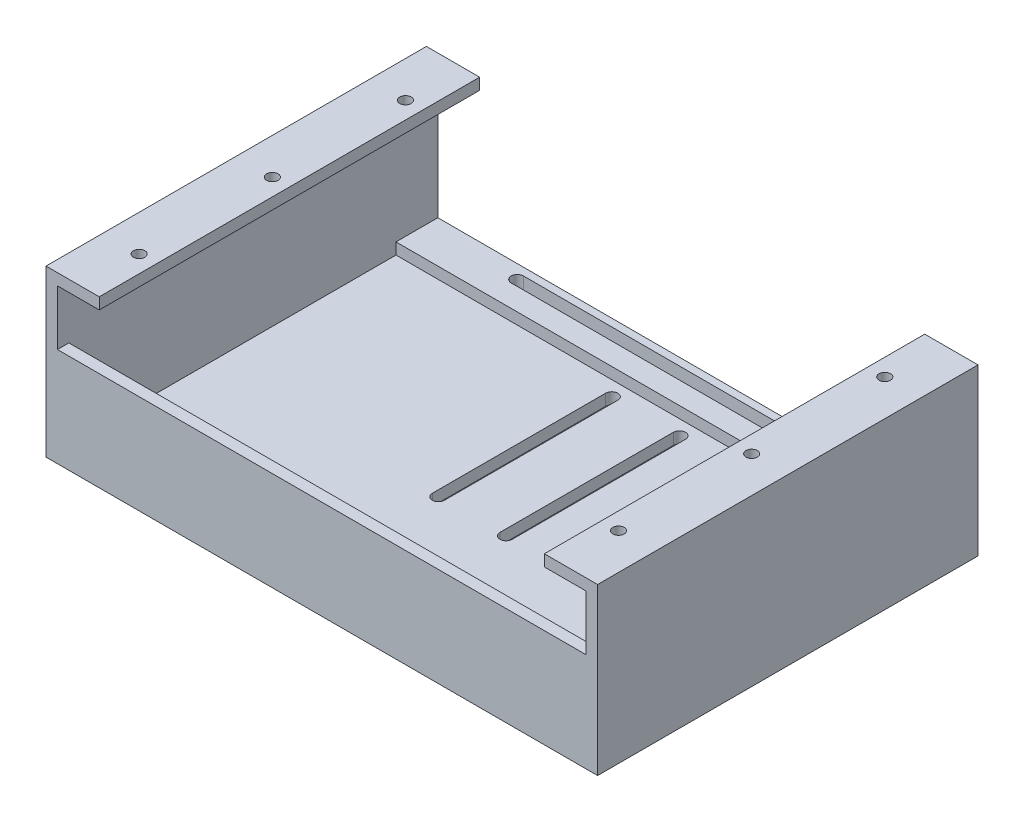
SolidWorks part; units mm, degrees
ref_plane "前视基准面" through (0, 0, 0) normal (0, 0, 1) x (1, 0, 0)
ref_plane "上视基准面" through (0, 0, 0) normal (0, 1, 0) x (1, 0, 0)
ref_plane "右视基准面" through (0, 0, 0) normal (1, 0, 0) x (0, 0, -1)
sketch "草图1" plane through (0, 0, 0) normal (0, 1, 0) x (1, 0, 0)
  line L1 (-72.5, 50) -> (72.5, 50)
  line L2 (-72.5, 50) -> (-72.5, -50)
  line L3 (-72.5, -50) -> (72.5, -50)
  line L4 (72.5, 50) -> (72.5, -50)
  line L5 (-72.5, 50) -> (72.5, -50) construction
  line L6 (-72.5, -50) -> (72.5, 50) construction
  point P0 (0, 0)
  dimension "D1" = 145
  dimension "D2" = 100
extrude "凸台-拉伸1" add sketch "草图1" along normal blind 3
sketch "草图2" plane through (0, 0, 0) normal (0, 1, 0) x (1, 0, 0)
  line L0 (-72.5, 50) -> (-69.5, 50)
  line L1 (72.5, 50) -> (-72.5, 50) construction
  line L2 (-69.5, 50) -> (-69.5, -50)
  line L3 (-72.5, -50) -> (72.5, -50) construction
  line L4 (-69.5, -50) -> (-72.5, -50)
  line L5 (-72.5, 50) -> (-72.5, -50) construction
  line L6 (-72.5, 50) -> (-72.5, -50)
  line L7 (0, 60.691) -> (0, -61.0101) construction
  line L8 (72.5, 50) -> (72.5, -50)
  line L9 (69.5, -50) -> (72.5, -50)
  line L10 (69.5, 50) -> (69.5, -50)
  line L11 (72.5, 50) -> (69.5, 50)
  dimension "D1" = 3
extrude "凸台-拉伸2" add sketch "草图2" along normal blind 40.5 from surface at 3 starting at face at (0, 3, 0)
sketch "草图3" plane through (0, 3, 0) normal (0, 1, 0) x (1, 0, 0)
  line L0 (-69.5, -50) -> (69.5, -50)
  line L1 (-69.5, -50) -> (69.5, -50) construction
  line L2 (69.5, -50) -> (69.5, -47)
  line L3 (69.5, -47) -> (-69.5, -47)
  line L4 (-69.5, 50) -> (-69.5, -50) construction
  line L5 (-69.5, -47) -> (-69.5, -50)
  dimension "D1" = 3
extrude "凸台-拉伸3" add sketch "草图3" along normal blind 23
sketch "草图4" plane through (0, 43.5, 0) normal (0, 1, 0) x (1, 0, 0)
  line L0 (-72.5, 50) -> (-58.5, 50)
  line L1 (-72.5, 50) -> (-69.5, 50) construction
  line L2 (-72.5, -50) -> (-72.5, 50) construction
  line L3 (69.5, 50) -> (-69.5, 50) construction
  line L4 (-58.5, 50) -> (-58.5, -50)
  line L5 (-69.5, -50) -> (69.5, -50) construction
  line L6 (-58.5, -50) -> (-72.5, -50)
  line L7 (-72.5, -50) -> (-72.5, 50)
  line L8 (0, 61.2498) -> (0, -56.9471) construction
  line L9 (72.5, -50) -> (72.5, 50)
  line L10 (58.5, -50) -> (72.5, -50)
  line L11 (58.5, 50) -> (58.5, -50)
  line L12 (72.5, 50) -> (58.5, 50)
  dimension "D1" = 14
extrude "凸台-拉伸4" add sketch "草图4" against normal blind 3
sketch "草图5" plane through (0, 43.5, 0) normal (0, 1, 0) x (1, 0, 0)
  line L0 (0, 70.1589) -> (0, -87.2886) construction
  line L1 (-72.5, 50) -> (-58.5, 50) construction
  line L2 (-58.5, -50) -> (-58.5, 50) construction
  circle A0 centre (-63, 35) radius 1.5
  circle A1 centre (-63, 0) radius 1.5
  circle A2 centre (-63, -35) radius 1.5
  circle A3 centre (63, -35) radius 1.5
  circle A4 centre (63, 0) radius 1.5
  circle A5 centre (63, 35) radius 1.5
  dimension "D1" = 15
  dimension "D2" = 3
  dimension "D3" = 35
  dimension "D4" = 35
  dimension "D5" = 4.5
extrude "切除-拉伸1" cut sketch "草图5" against normal up to next
sketch "草图6" plane through (0, 0, 0) normal (0, -1, 0) x (1, 0, 0)
  line L0 (0, 35.4338) -> (0, -55.998) construction
  line L1 (-8.9, 10.4483) -> (-8.9, -35.1174) construction
  line L2 (-7.3, 10.4483) -> (-7.3, -35.1174)
  line L3 (-10.5, 10.4483) -> (-10.5, -35.1174)
  line L4 (8.9, 10.4483) -> (8.9, -35.1174) construction
  line L5 (7.3, 10.4483) -> (7.3, -35.1174)
  line L6 (10.5, 10.4483) -> (10.5, -35.1174)
  arc A0 (-7.3, 10.4483) -> (-10.5, 10.4483) centre (-8.9, 10.4483) ccw
  arc A1 (-10.5, -35.1174) -> (-7.3, -35.1174) centre (-8.9, -35.1174) ccw
  arc A2 (7.3, 10.4483) -> (10.5, 10.4483) centre (8.9, 10.4483) cw
  arc A3 (10.5, -35.1174) -> (7.3, -35.1174) centre (8.9, -35.1174) cw
  point P5 (-8.9, -12.3346)
  point P12 (8.9, -12.3346)
  dimension "D1" = 1.6
  dimension "D2" = 10.5
extrude "切除-拉伸2" cut sketch "草图6" against normal up to next
sketch "草图7" plane through (69.5, 0, 0) normal (-1, 0, 0) x (0, 0, 1)
  line L0 (-50, 43.5) -> (-50, 0) construction
  line L1 (-50, 6) -> (-39, 6)
  line L2 (-50, 6) -> (-50, 3)
  line L3 (-50, 3) -> (-39, 3)
  line L4 (-39, 6) -> (-39, 3)
  line L5 (-50, 6) -> (-39, 3) construction
  line L6 (-50, 3) -> (-39, 6) construction
  line L8 (-50, 0) -> (50, 0) construction
  point P0 (-44.5, 4.5)
  dimension "D1" = 3
  dimension "D2" = 11
  dimension "D3" = 3
extrude "凸台-拉伸5" add sketch "草图7" along normal up to next
sketch "草图8" plane through (0, 6, 0) normal (0, 1, 0) x (1, 0, 0)
  line L0 (-58.5, 46.4) -> (57.7386, 46.4) construction
  line L1 (-58.5, -50) -> (-58.5, 50) construction
  line L2 (-69.5, 39) -> (69.5, 39) construction
  line L3 (-45, 46.4) -> (45, 46.4) construction
  line L4 (-45, 48) -> (45, 48)
  line L5 (-45, 44.8) -> (45, 44.8)
  line L6 (0, 0) -> (0, 61.9965) construction
  arc A0 (-45, 48) -> (-45, 44.8) centre (-45, 46.4) ccw
  arc A1 (45, 44.8) -> (45, 48) centre (45, 46.4) ccw
  point P8 (0, 46.4)
  point P13 (0, 0)
  dimension "D2" = 1.6
  dimension "D1" = 7.4
  dimension "D3" = 90
extrude "切除-拉伸3" cut sketch "草图8" against normal up to next
